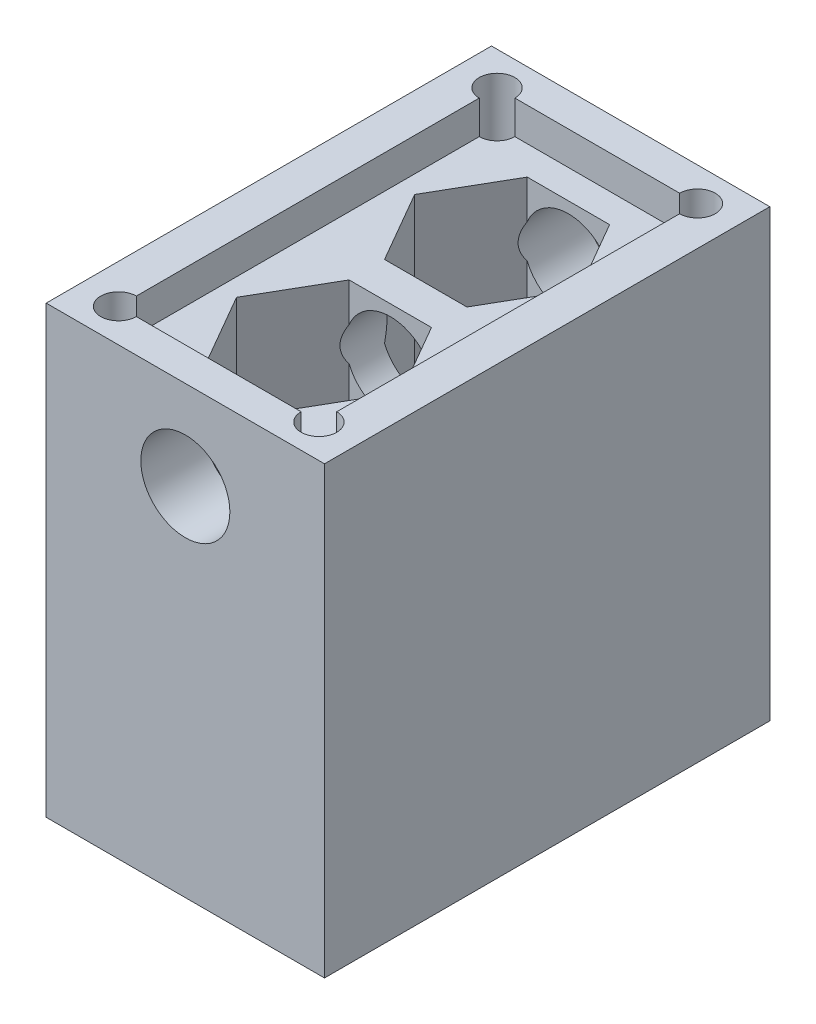
SolidWorks part; units mm, degrees
ref_plane "Спереди" through (0, 0, 0) normal (0, 0, 1) x (1, 0, 0)
ref_plane "Сверху" through (0, 0, 0) normal (0, 1, 0) x (1, 0, 0)
ref_plane "Справа" through (0, 0, 0) normal (1, 0, 0) x (0, 0, -1)
sketch "Sketch1" plane through (0, 0, 0) normal (0, 1, 0) x (1, 0, 0)
  line L1 (12.5, -20) -> (-12.5, -20)
  line L2 (12.5, -20) -> (12.5, 20)
  line L3 (12.5, 20) -> (-12.5, 20)
  line L4 (-12.5, -20) -> (-12.5, 20)
  line L5 (12.5, -20) -> (-12.5, 20) construction
  line L6 (12.5, 20) -> (-12.5, -20) construction
  point P0 (0, 0)
  dimension "D1" = 25
  dimension "D2" = 40
extrude "Boss-Extrude1" add sketch "Sketch1" along normal blind 40
sketch "Sketch2" plane through (0, 0, 20) normal (0, 0, 1) x (1, 0, 0)
  line L0 (-12.5, 32) -> (12.5, 32) construction
  line L1 (-12.5, 40) -> (-12.5, 0) construction
  line L2 (12.5, 40) -> (12.5, 0) construction
  line L3 (-12.5, 40) -> (12.5, 40) construction
  circle A0 centre (0, 32) radius 4
  dimension "D1" = 8
  dimension "D2" = 8
extrude "Cut-Extrude1" cut sketch "Sketch2" against normal through all
sketch "Sketch4" plane through (0, 40, 0) normal (0, 1, 0) x (1, 0, 0)
  line L0 (0, 20) -> (0, -20) construction
  line L1 (12.5, 20) -> (-12.5, 20) construction
  line L2 (-12.5, -20) -> (12.5, -20) construction
  circle A0 centre (0, -8) radius 4.15
  circle A1 centre (0, 8) radius 4.15
  point P3 (0, 0)
  point P13 (2.9828, -5.6261)
  dimension "D1" = 8.3
  dimension "D2" = 16
  dimension "D3" = 8
extrude "Cut-Extrude2" cut sketch "Sketch4" against normal through all
sketch "Sketch5" plane through (0, 40, 0) normal (0, 1, 0) x (1, 0, 0)
  line L1 (-3.7, -14.4086) -> (3.7, -14.4086)
  line L2 (3.7, -14.4086) -> (7.4, -8)
  line L3 (7.4, -8) -> (3.7, -1.5914)
  line L4 (3.7, -1.5914) -> (-3.7, -1.5914)
  line L5 (-3.7, -1.5914) -> (-7.4, -8)
  line L6 (-7.4, -8) -> (-3.7, -14.4086)
  line L7 (-12.5, -20) -> (12.5, -20) construction
  line L8 (-3.7, 14.4086) -> (-7.4, 8)
  line L9 (-7.4, 8) -> (-3.7, 1.5914)
  line L10 (-3.7, 1.5914) -> (3.7, 1.5914)
  line L11 (3.7, 1.5914) -> (7.4, 8)
  line L12 (7.4, 8) -> (3.7, 14.4086)
  line L13 (3.7, 14.4086) -> (-3.7, 14.4086)
  circle A0 centre (0, -8) radius 7.4 construction
  circle A1 centre (0, 8) radius 7.4 construction
  dimension "D1" = 14.8
extrude "Cut-Extrude3" cut sketch "Sketch5" against normal blind 18
sketch "Sketch6" plane through (0, 40, 0) normal (0, 1, 0) x (1, 0, 0)
  line L1 (-9, 17) -> (9, 17) construction
  line L2 (-9, 17) -> (-9, -17) construction
  line L3 (-9, -17) -> (9, -17) construction
  line L4 (9, 17) -> (9, -17) construction
  line L5 (-9, 17) -> (9, -17) construction
  line L6 (-9, -17) -> (9, 17) construction
  circle A0 centre (9, -17) radius 1.6
  circle A1 centre (-9, -17) radius 1.6
  circle A2 centre (-9, 17) radius 1.6
  circle A3 centre (9, 17) radius 1.6
  point P0 (0, 0)
  dimension "D1" = 3.2
  dimension "D2" = 18
  dimension "D3" = 34
extrude "Cut-Extrude4" cut sketch "Sketch6" against normal through all
sketch "Sketch7" plane through (0, 40, 0) normal (0, 1, 0) x (1, 0, 0)
  line L1 (-9, 17) -> (9, 17)
  line L2 (-9, 17) -> (-9, -17)
  line L3 (-9, -17) -> (9, -17)
  line L4 (9, 17) -> (9, -17)
  line L5 (-9, 17) -> (9, -17) construction
  line L6 (-9, -17) -> (9, 17) construction
  point P0 (0, 0)
  dimension "D1" = 18
extrude "Cut-Extrude5" cut sketch "Sketch7" against normal blind 3
sketch "Sketch8" plane through (0, 0, 0) normal (0, -1, 0) x (1, 0, 0)
  circle A0 centre (0, -8) radius 7.5 construction
  circle A1 centre (0, 8) radius 7.5 construction
  dimension "D1" = 15
